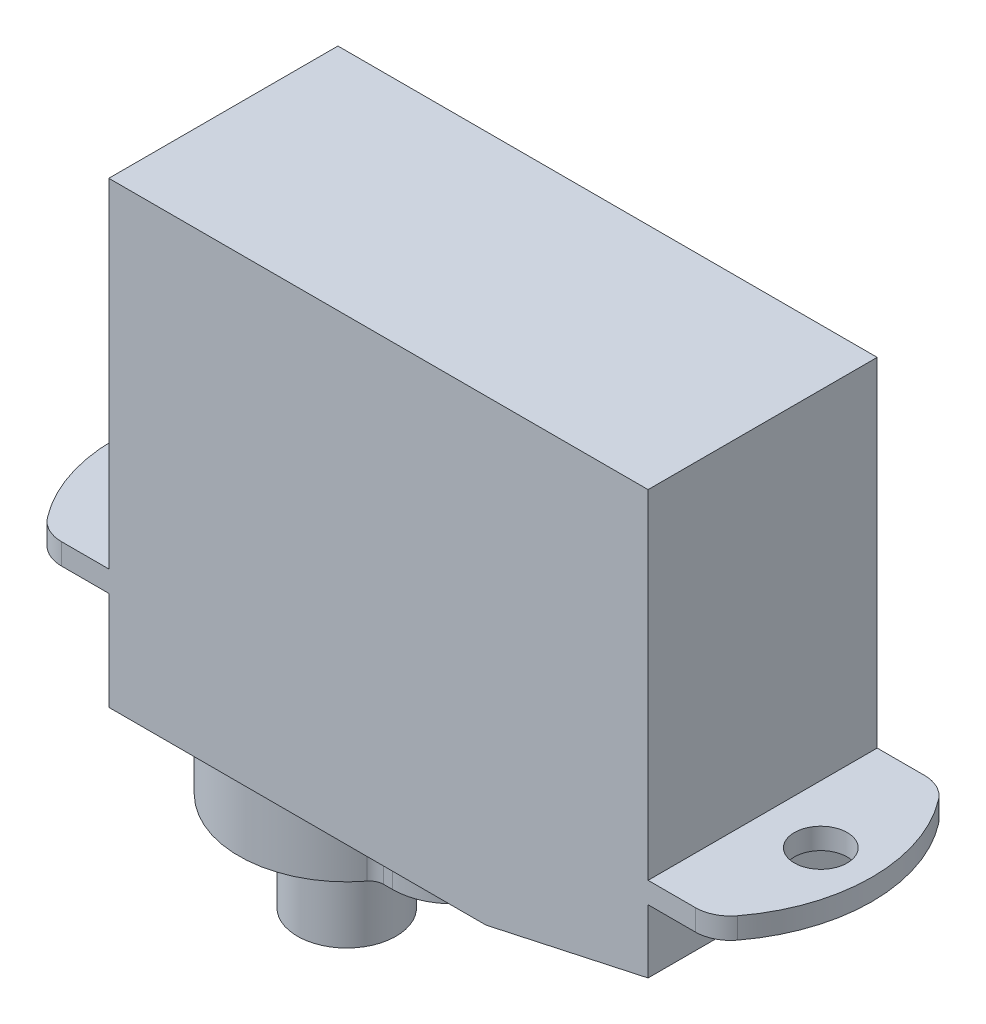
SolidWorks part; units mm, degrees
ref_plane "Front Plane" through (0, 0, 0) normal (0, 0, 1) x (1, 0, 0)
ref_plane "Top Plane" through (0, 0, 0) normal (0, 1, 0) x (1, 0, 0)
ref_plane "Right Plane" through (0, 0, 0) normal (1, 0, 0) x (0, 0, -1)
sketch "Sketch1" plane through (0, 0, 0) normal (0, 1, 0) x (1, 0, 0)
  line L1 (9.7155, -4.1275) -> (-9.7155, -4.1275)
  line L2 (9.7155, -4.1275) -> (9.7155, 4.1275)
  line L3 (9.7155, 4.1275) -> (-9.7155, 4.1275)
  line L4 (-9.7155, -4.1275) -> (-9.7155, 4.1275)
  line L5 (9.7155, -4.1275) -> (-9.7155, 4.1275) construction
  line L6 (9.7155, 4.1275) -> (-9.7155, -4.1275) construction
  point P0 (0, 0)
  dimension "D1" = 19.431
  dimension "D2" = 8.255
extrude "Boss-Extrude1" add sketch "Sketch1" along normal blind 16.51
ref_plane "Plane1" through (0, 4.318, 0) normal (0, 1, 0) x (1, 0, 0)
sketch "Sketch2" plane through (0, 4.318, 0) normal (0, 1, 0) x (1, 0, 0)
  line L0 (9.7155, -4.1275) -> (9.7155, 4.1275) construction
  line L1 (-9.7155, 4.1275) -> (-9.7155, -4.1275) construction
  line L2 (9.7155, -4.1275) -> (9.7155, 4.1275)
  line L3 (-9.7155, 4.1275) -> (-9.7155, -4.1275)
  line L4 (0, 0) -> (0, 6.6742) construction
  line L5 (9.7155, 4.1275) -> (11.4179, 4.1275)
  line L6 (9.7155, -4.1275) -> (11.4179, -4.1275)
  line L7 (-9.7155, -4.1275) -> (-11.4179, -4.1275)
  line L8 (-9.7155, 4.1275) -> (-11.4179, 4.1275)
  arc A0 (12.4281, 3.6272) -> (12.4281, -3.6272) centre (7.6676, 0) cw
  arc A1 (-12.4281, 3.6272) -> (-12.4281, -3.6272) centre (-7.6676, 0) ccw
  circle A2 centre (11.811, 0) radius 0.9525
  circle A3 centre (-11.811, 0) radius 0.9525
  arc A4 (-12.4281, 3.6272) -> (-11.4179, 4.1275) centre (-11.4179, 2.8575) cw
  arc A5 (-11.4179, -4.1275) -> (-12.4281, -3.6272) centre (-11.4179, -2.8575) cw
  arc A6 (11.4179, -4.1275) -> (12.4281, -3.6272) centre (11.4179, -2.8575) ccw
  arc A7 (11.4179, 4.1275) -> (12.4281, 3.6272) centre (11.4179, 2.8575) cw
  point P19 (-12.0015, 4.1275)
  point P22 (-12.0015, -4.1275)
  point P25 (12.0015, -4.1275)
  point P28 (12.0015, 4.1275)
  dimension "D2" = 3.937
  dimension "D3" = 23.622
  dimension "D4" = 1.905
  dimension "D5" = 1.27
  dimension "D1" = 2.286
extrude "Boss-Extrude2" add sketch "Sketch2" against normal blind 0.762
sketch "Sketch3" plane through (0, 0, 4.1275) normal (0, 0, 1) x (1, 0, 0)
  line L0 (9.7155, 16.51) -> (9.7155, 1.27) construction
  line L1 (9.7155, 3.556) -> (9.7155, 0) construction
  line L2 (9.7155, 0) -> (3.8735, 0)
  line L3 (-9.7155, 0) -> (9.7155, 0) construction
  line L4 (9.7155, 1.27) -> (3.8735, 0)
  line L5 (9.7155, 1.27) -> (9.7155, 0)
  dimension "D1" = 15.24
  dimension "D2" = 5.842
extrude "Cut-Extrude1" cut sketch "Sketch3" against normal through all
sketch "Sketch4" plane through (0, 0, 0) normal (0, -1, 0) x (1, 0, 0)
  line L0 (-9.7155, 4.1275) -> (-9.7155, -4.1275) construction
  line L1 (-1.4605, 2.159) -> (-1.7782, 2.159)
  line L2 (-1.4605, -2.159) -> (-1.7782, -2.159)
  arc A0 (-2.1819, 2.3587) -> (-2.1819, -2.3587) centre (-5.2705, 0) ccw
  arc A1 (-1.4605, -2.159) -> (-1.4605, 2.159) centre (-1.4605, 0) ccw
  arc A2 (-1.7782, -2.159) -> (-2.1819, -2.3587) centre (-1.7782, -2.667) ccw
  arc A3 (-1.7782, 2.159) -> (-2.1819, 2.3587) centre (-1.7782, 2.667) cw
  dimension "D1" = 7.7724
  dimension "D3" = 4.318
  dimension "D5" = 0.508
  dimension "D2" = 4.445
  dimension "D4" = 3.81
extrude "Boss-Extrude3" add sketch "Sketch4" along normal blind 2.54
sketch "Sketch5" plane through (0, -2.54, 0) normal (0, -1, 0) x (1, 0, 0)
  arc A0 (-2.1819, 2.3587) -> (-2.1819, -2.3587) centre (-5.2705, 0) ccw construction
  arc A1 (-2.1819, 2.3587) -> (-2.1819, -2.3587) centre (-5.2705, 0) ccw construction
  circle A2 centre (-5.2705, 0) radius 1.778
  dimension "D1" = 3.556
extrude "Boss-Extrude4" add sketch "Sketch5" along normal blind 3.556
